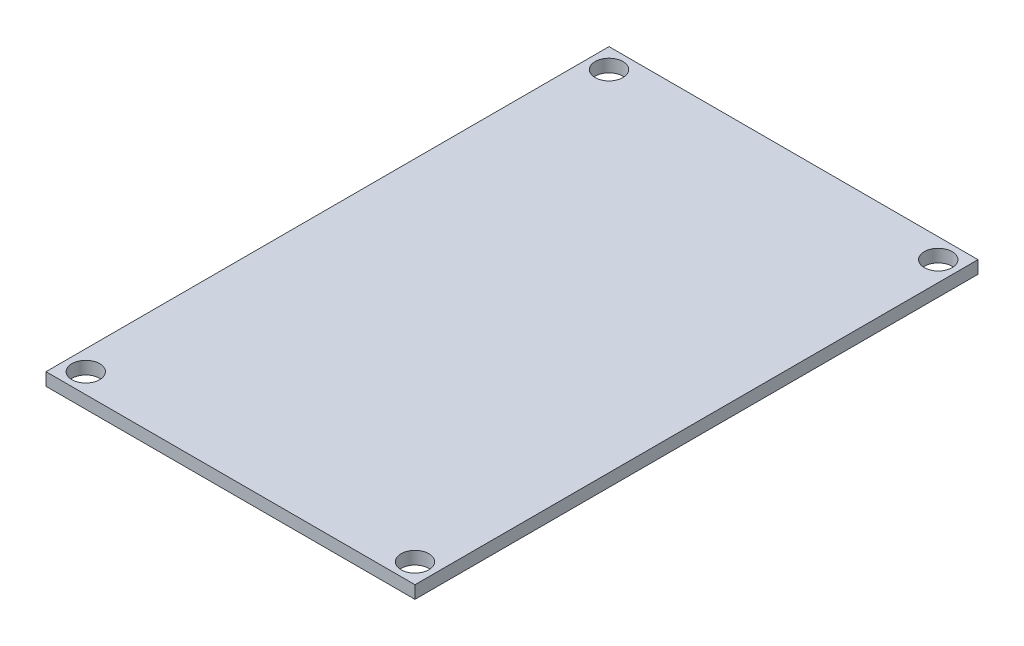
SolidWorks part; units mm, degrees
ref_plane "Front Plane" through (0, 0, 0) normal (0, 0, 1) x (1, 0, 0)
ref_plane "Top Plane" through (0, 0, 0) normal (0, 1, 0) x (1, 0, 0)
ref_plane "Right Plane" through (0, 0, 0) normal (1, 0, 0) x (0, 0, -1)
sketch "Sketch1" plane through (0, 0, 0) normal (0, 1, 0) x (1, 0, 0)
  line L1 (-23.5712, 35.9664) -> (23.5712, 35.9664)
  line L2 (-23.5712, 35.9664) -> (-23.5712, -35.9664)
  line L3 (-23.5712, -35.9664) -> (23.5712, -35.9664)
  line L4 (23.5712, 35.9664) -> (23.5712, -35.9664)
  line L5 (-23.5712, 35.9664) -> (23.5712, -35.9664) construction
  line L6 (-23.5712, -35.9664) -> (23.5712, 35.9664) construction
  point P0 (0, 0)
  dimension "D1" = 47.1424
  dimension "D2" = 71.9328
extrude "Boss-Extrude1" add sketch "Sketch1" along normal blind 1.6256
sketch "Sketch2" plane through (0, 1.6256, 0) normal (0, 1, 0) x (1, 0, 0)
  line L0 (23.5712, 35.9664) -> (-23.5712, 35.9664) construction
  line L1 (-23.5712, 35.9664) -> (-23.5712, -35.9664) construction
  line L2 (-23.5712, -35.9664) -> (23.5712, -35.9664) construction
  line L3 (23.5712, -35.9664) -> (23.5712, 35.9664) construction
  circle A0 centre (-21.0312, 33.4264) radius 1.778
  circle A1 centre (21.0312, 33.4264) radius 1.778
  circle A2 centre (-21.0312, -33.4264) radius 1.778
  circle A3 centre (21.0312, -33.4264) radius 1.778
  dimension "D1" = 3.556
  dimension "D2" = 2.54
  dimension "D3" = 2.54
  dimension "D4" = 3.556
  dimension "D5" = 2.54
  dimension "D7" = 3.556
  dimension "D8" = 2.54
  dimension "D9" = 2.54
  dimension "D10" = 3.556
  dimension "D11" = 2.54
  dimension "D12" = 2.54
  dimension "D6" = 2.54
extrude "Cut-Extrude1" cut sketch "Sketch2" against normal blind 1.6256
